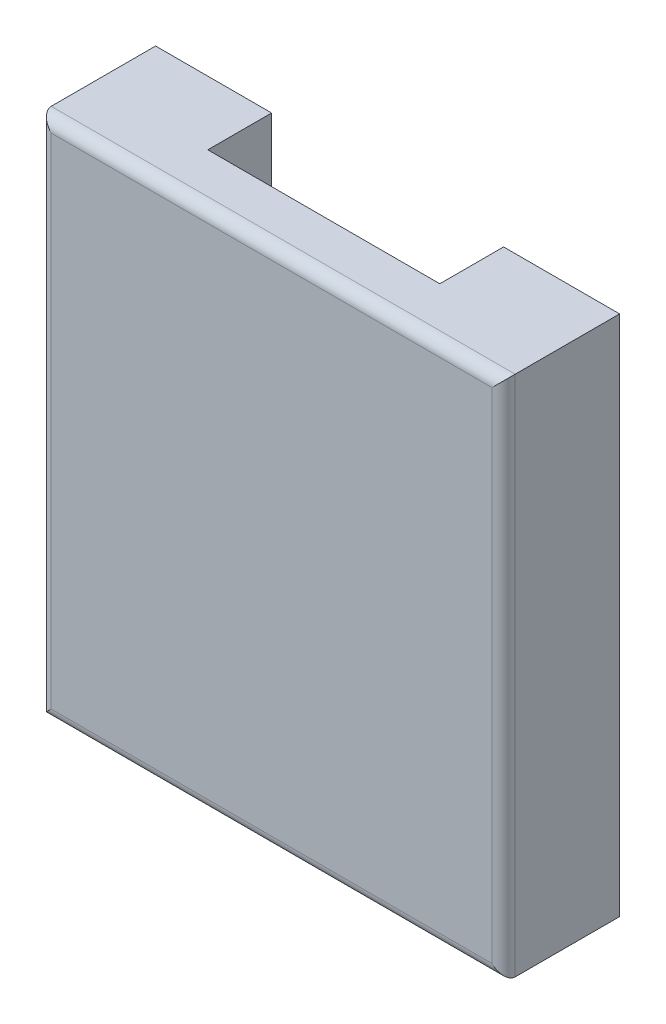
SolidWorks part; units mm, degrees
other "Marca1"
sketch "Croquis3"
ref_plane "Alzado" through (0, 0, 0) normal (0, 0, 1) x (1, 0, 0)
ref_plane "Planta" through (0, 0, 0) normal (0, 1, 0) x (1, 0, 0)
ref_plane "Vista lateral" through (0, 0, 0) normal (1, 0, 0) x (0, 0, -1)
sketch "Croquis1" plane through (0, 0, 0) normal (0, 0, 1) x (1, 0, 0)
  line L1 (-20, 22.5) -> (20, 22.5)
  line L2 (-20, 22.5) -> (-20, -22.5)
  line L3 (-20, -22.5) -> (20, -22.5)
  line L4 (20, 22.5) -> (20, -22.5)
  line L5 (-20, 22.5) -> (20, -22.5) construction
  line L6 (-20, -22.5) -> (20, 22.5) construction
  point P0 (0, 0)
  dimension "D1" = 45
  dimension "D2" = 40
extrude "Saliente-Extruir1" add sketch "Croquis1" along normal blind 4.5
sketch "Croquis2" plane through (0, 0, 0) normal (0, 0, -1) x (-1, 0, 0)
  line L0 (20, -22.5) -> (-20, -22.5) construction
  line L1 (-20, 22.5) -> (-10, 22.5)
  line L2 (-20, 22.5) -> (-20, -22.5)
  line L3 (-20, -22.5) -> (-10, -22.5)
  line L4 (-10, 22.5) -> (-10, -22.5)
  line L5 (0, 0) -> (0, -8.6205) construction
  line L6 (10, 22.5) -> (10, -22.5)
  line L7 (20, -22.5) -> (10, -22.5)
  line L8 (20, 22.5) -> (20, -22.5)
  line L9 (20, 22.5) -> (10, 22.5)
  dimension "D1" = 10
extrude "Saliente-Extruir2" add sketch "Croquis2" along normal blind 5.5
fillet "Redondeo1" radius 1 4 edges at (0, -22.5, 4.5) (-20, 0, 4.5) (0, 22.5, 4.5) (20, 0, 4.5)
